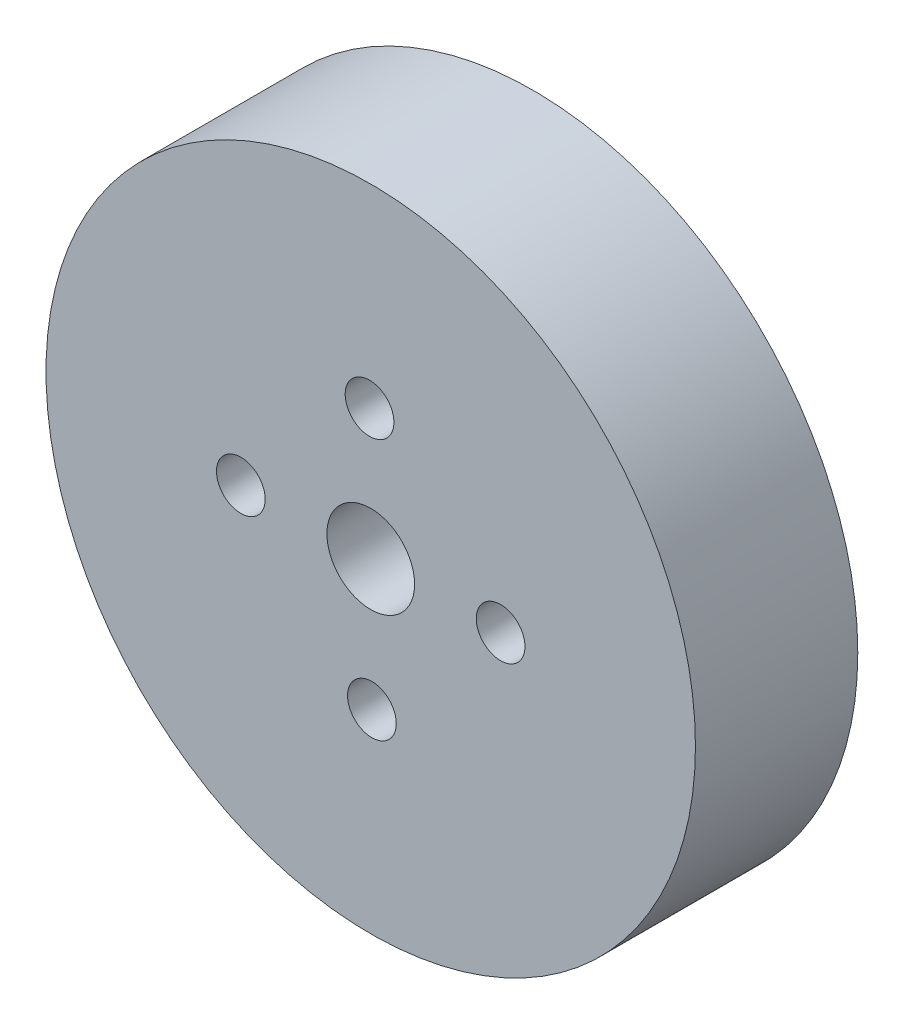
SolidWorks part; units mm, degrees
ref_plane "Front" through (0, 0, 0) normal (0, 0, 1) x (1, 0, 0)
ref_plane "Top" through (0, 0, 0) normal (0, 1, 0) x (1, 0, 0)
ref_plane "Right" through (0, 0, 0) normal (1, 0, 0) x (0, 0, -1)
sketch "Sketch1" plane through (0, 0, 0) normal (0, 0, 1) x (1, 0, 0)
  circle A0 centre (0, 0) radius 20
  circle A2 centre (-8, -0.0726) radius 1.5
  circle A3 centre (-0.0726, 8) radius 1.5
  circle A4 centre (8, 0.0726) radius 1.5
  circle A5 centre (0.0726, -8) radius 1.5
  circle A6 centre (0, 0) radius 2.7
  point P15 (0, 0)
  dimension "D1" = 40
  dimension "D2" = 8
  dimension "D3" = 3
  dimension "D5" = 5.4
  dimension "D4" = 4
extrude "Boss-Extrude1" add sketch "Sketch1" along normal blind 10
